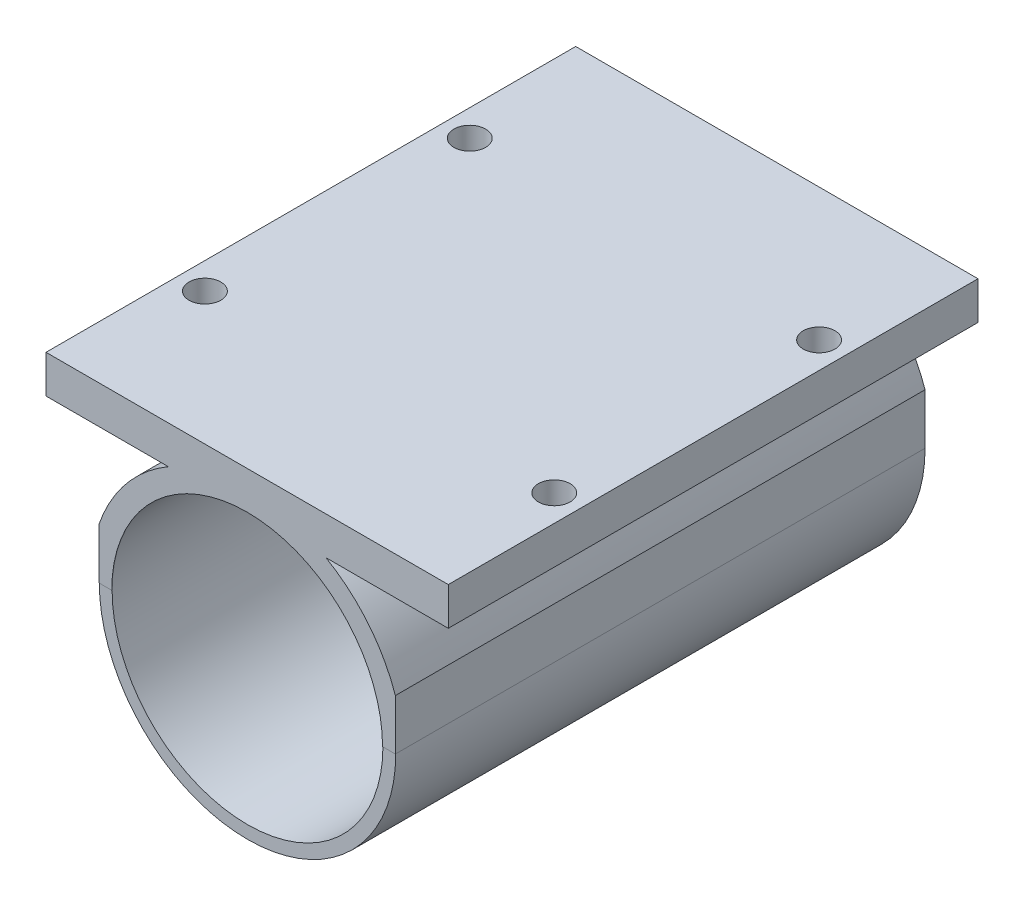
SolidWorks part; units mm, degrees
ref_plane "Front Plane" through (0, 0, 0) normal (0, 0, 1) x (1, 0, 0)
ref_plane "Top Plane" through (0, 0, 0) normal (0, 1, 0) x (1, 0, 0)
ref_plane "Right Plane" through (0, 0, 0) normal (1, 0, 0) x (0, 0, -1)
sketch "Sketch1" plane through (0, 0, 0) normal (0, 0, 1) x (1, 0, 0)
  circle A0 centre (0, 0) radius 14
  dimension "D1" = 28
extrude "Boss-Extrude1" add sketch "Sketch1" along normal blind 50
sketch "Sketch5" plane through (0, 0, 0) normal (0, 1, 0) x (1, 0, 0)
  line L0 (-14, 0) -> (14, 0)
  line L1 (-14, 0) -> (-14, -50.0349)
  line L2 (14, 0) -> (14, -50.0349)
  line L3 (-14, -50.0349) -> (14, -50.0349)
extrude "Boss-Extrude2" add sketch "Sketch5" along normal blind 21
sketch "Sketch2" plane through (0, 0, 50) normal (0, 0, 1) x (1, 0, 0)
  circle A0 centre (0, 0) radius 12.7918
  circle A1 centre (0, 0) radius 14 construction
  dimension "D1" = 1.2082
  dimension "D2" = 1.2082
extrude "Cut-Extrude1" cut sketch "Sketch2" against normal blind 48 contours A0
sketch "Sketch3" plane through (0, 0, 0) normal (0, 0, -1) x (-1, 0, 0)
  circle A0 centre (0, 0) radius 4
  dimension "D1" = 8
extrude "Cut-Extrude2" cut sketch "Sketch3" against normal blind 49
sketch "Sketch4" plane through (0, 0, 0) normal (0, 0, -1) x (-1, 0, 0)
  line L0 (-14, 0) -> (14, 0) construction
  line L1 (0, 14) -> (0, -14) construction
  line L2 (14, 0) -> (0, 14) construction
  line L3 (0, 14) -> (7, 7) construction
  line L4 (7, 7) -> (-9.8995, -9.8995) construction
  circle A0 centre (0, 0) radius 14 construction
  circle A1 centre (0, -8.5) radius 1.5
  circle A2 centre (0, 8.5) radius 1.5
  circle A3 centre (8.5, 0) radius 1.5
  circle A4 centre (-8.5, 0) radius 1.5
  dimension "D1" = 8.5
  dimension "D2" = 8.5
  dimension "D3" = 45
  dimension "D4" = 8.5
  dimension "D5" = 8.5
extrude "Cut-Extrude3" cut sketch "Sketch4" against normal blind 49
sketch "Sketch6" plane through (0, 0, 50.0349) normal (0, 0, 1) x (1, 0, 0)
  circle A1 centre (0, 0) radius 12.79
extrude "Cut-Extrude5" cut sketch "Sketch6" against normal blind 21
sketch "Sketch7" plane through (0, 0, 50.0349) normal (0, 0, 1) x (1, 0, 0)
  line L0 (-14, 21) -> (14, 21)
  line L1 (-14, 21) -> (-14, 16.3653)
  line L2 (14, 21) -> (14, 16.3653)
  line L3 (-14, 16.3653) -> (14, 16.3653)
extrude "Cut-Extrude6" cut sketch "Sketch7" against normal blind 53
sketch "Sketch8" plane through (14, 0, 0) normal (1, 0, 0) x (0, 0, -1)
  line L0 (-50.0349, 16.3653) -> (0, 16.3653)
  line L1 (-50.0349, 16.3653) -> (-50.0349, 12.7853)
  line L2 (0, 16.3653) -> (0, 12.7853)
  line L3 (-50.0349, 12.7853) -> (0, 12.7853)
  dimension "D1" = 3.58
extrude "Boss-Extrude3" add sketch "Sketch8" along normal blind 5
sketch "Sketch13" plane through (0, 12.7853, 0) normal (0, -1, 0) x (1, 0, 0)
  line L0 (16.5, 50.0349) -> (16.5, 0) construction
  line L1 (19, 50.0349) -> (14, 50.0349) construction
  line L2 (19, 0) -> (14, 0) construction
  line L3 (14, 25.0174) -> (19, 25.0174) construction
  line L4 (14, 50.0349) -> (14, 0) construction
  line L5 (19, 50.0349) -> (19, 0) construction
  line L6 (14, 25.0174) -> (19, 50.0349) construction
  line L7 (14, 25.0174) -> (19, 0) construction
  circle A0 centre (16.5, 37.5262) radius 1.5
  circle A1 centre (16.5, 12.5087) radius 1.5
  dimension "D1" = 5
extrude "Cut-Extrude7" cut sketch "Sketch13" against normal blind 5
sketch "Sketch14" plane through (-14, 0, 0) normal (-1, 0, 0) x (0, 0, 1)
  line L0 (0, 16.3653) -> (50.0349, 16.3653)
  line L1 (0, 16.3653) -> (0, 12.7853)
  line L2 (50.0349, 16.3653) -> (50.0349, 12.7853)
  line L3 (0, 12.7853) -> (50.0349, 12.7853)
  dimension "D1" = 3.58
extrude "Boss-Extrude4" add sketch "Sketch14" along normal blind 5
sketch "Sketch15" plane through (0, 12.7853, 0) normal (0, -1, 0) x (1, 0, 0)
  line L0 (-16.5, 0) -> (-16.5, 50.0349) construction
  line L1 (-19, 0) -> (-14, 0) construction
  line L2 (-19, 50.0349) -> (-14, 50.0349) construction
  line L3 (-19, 25.0174) -> (-14, 25.0174) construction
  line L4 (-19, 0) -> (-19, 50.0349) construction
  line L5 (-14, 0) -> (-14, 50.0349) construction
  line L6 (-14, 0) -> (-19, 25.0174) construction
  line L7 (-19, 25.0174) -> (-14, 50.0349) construction
  circle A0 centre (-16.5, 12.5087) radius 1.5
  circle A1 centre (-16.5, 37.5262) radius 1.5
extrude "Cut-Extrude8" cut sketch "Sketch15" against normal blind 5
fillet "Fillet1" radius 1 1 edges at (10, 0, 0)
fillet "Fillet2" radius 1 3 edges at (1.5, 8.5, 0) (-10, 0, 0) (-1.5, -8.5, 0)
sketch "Sketch16" plane through (0, 0, 0) normal (0, 0, -1) x (-1, 0, 0)
  line L0 (14, 12.7853) -> (-14, 12.7853) construction
  line L1 (-14, 12.7853) -> (-14, 4.7853) construction
  line L2 (-14, 12.7853) -> (-14, 0) construction
  line L3 (-7.4455, 12.7853) -> (-14, 12.7853)
  line L4 (-14, 12.7853) -> (-14, 4.7853)
  line L5 (0, 0) -> (0, 12.7853) construction
  line L6 (14, 12.7853) -> (14, 4.7853)
  line L7 (7.4455, 12.7853) -> (14, 12.7853)
  arc A0 (-14, 4.7853) -> (-7.4455, 12.7853) centre (0, 0) cw
  arc A1 (14, 4.7853) -> (7.4455, 12.7853) centre (0, 0) ccw
  dimension "D1" = 8
extrude "Cut-Extrude9" cut sketch "Sketch16" against normal blind 73
